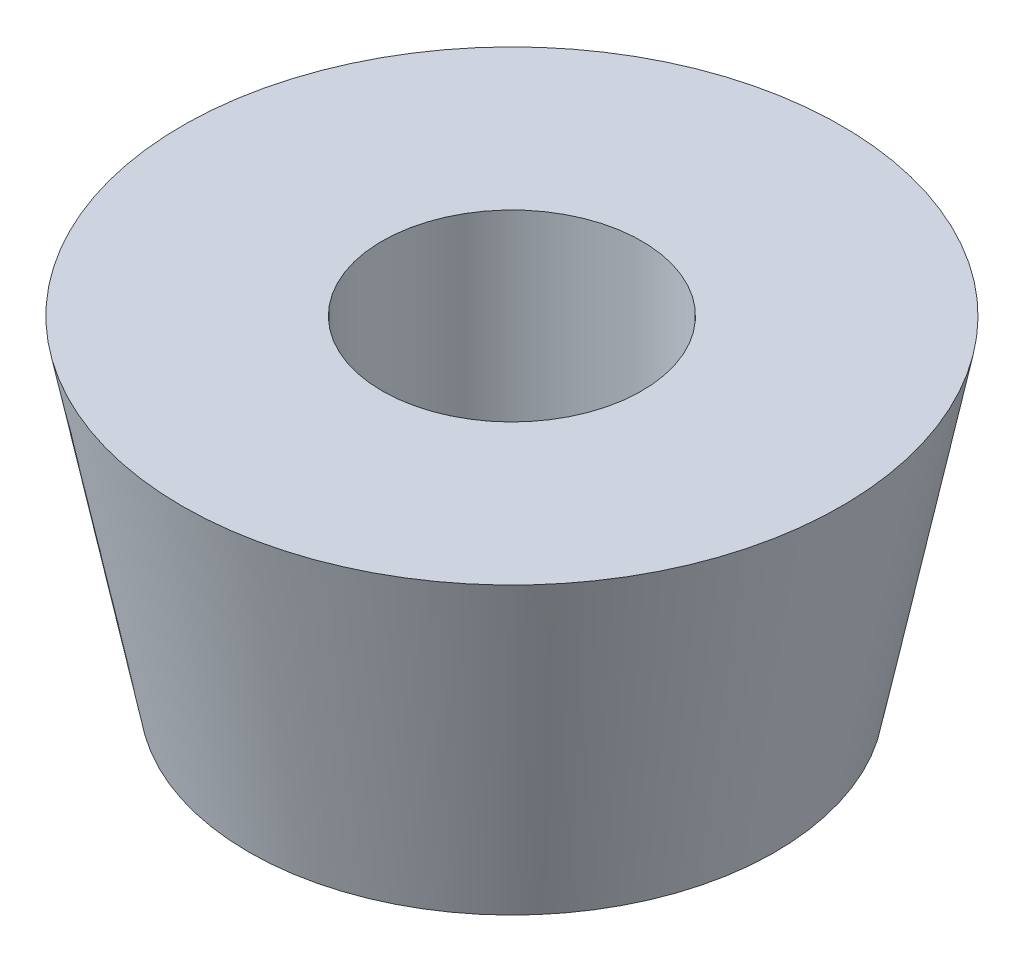
SolidWorks part; units mm, degrees
ref_plane "Front Plane" through (0, 0, 0) normal (0, 0, 1) x (1, 0, 0)
ref_plane "Top Plane" through (0, 0, 0) normal (0, 1, 0) x (1, 0, 0)
ref_plane "Right Plane" through (0, 0, 0) normal (1, 0, 0) x (0, 0, -1)
sketch "Sketch1" plane through (0, 0, 0) normal (0, 0, 1) x (1, 0, 0)
  line L0 (0, 0) -> (0, -5) construction
  line L1 (1.95, 0) -> (1.95, -5)
  line L2 (1.95, -5) -> (3.95, -5)
  line L3 (3.95, -5) -> (4.95, 0)
  line L4 (4.95, 0) -> (1.95, 0)
  dimension "D1" = 5
  dimension "D2" = 3
  dimension "D3" = 2
  dimension "D4" = 3.9
revolve "Revolve1" add sketch "Sketch1" angle 360 about L0
